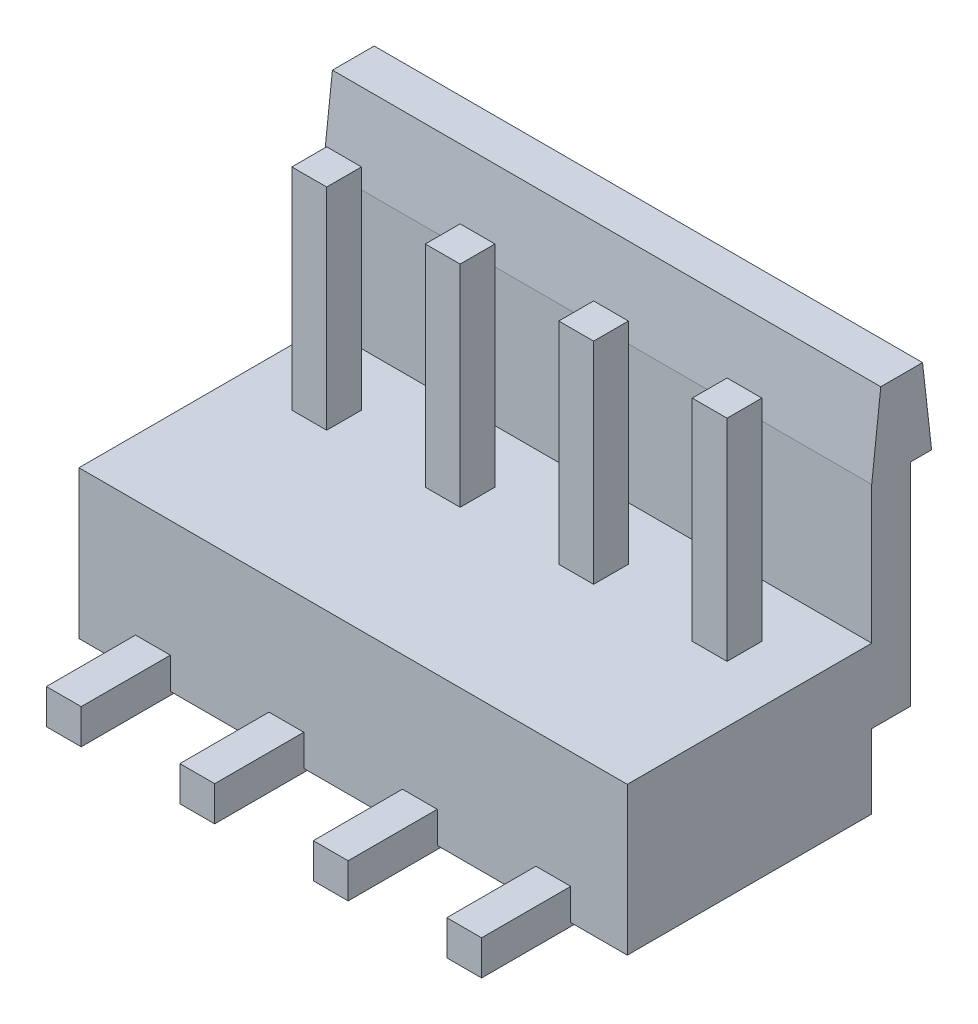
SolidWorks part; units mm, degrees
ref_plane "Front Plane" through (0, 0, 0) normal (0, 0, 1) x (1, 0, 0)
ref_plane "Top Plane" through (0, 0, 0) normal (0, 1, 0) x (1, 0, 0)
ref_plane "Right Plane" through (0, 0, 0) normal (1, 0, 0) x (0, 0, -1)
sketch "Sketch2" plane through (0, 0, 0) normal (1, 0, 0) x (0, 0, -1)
  line L0 (0, 0) -> (0, 3.95)
  line L1 (-7.02, 0) -> (0, 0)
  line L2 (-7.02, 0) -> (-7.02, -4.25)
  line L3 (-7.02, -4.25) -> (0, -4.25)
  line L4 (0, 0) -> (0, -4.25)
  line L5 (0, 3.95) -> (0.26, 6.25)
  line L6 (0.26, 6.25) -> (1.46, 6.25)
  line L7 (1.46, 6.25) -> (1.72, 3.95)
  line L8 (1.72, 3.95) -> (1.12, 3.95)
  line L9 (1.12, 3.95) -> (1.12, -2.125)
  line L10 (1.12, -2.125) -> (0, -2.125)
  dimension "D1" = 1.72
  dimension "D2" = 10.5
  dimension "D3" = 6.25
  dimension "D4" = 2.3
  dimension "D5" = 1.2
  dimension "D6" = 1.12
  dimension "D7" = 8.14
extrude "Boss-Extrude1" add sketch "Sketch2" along normal mid plane 15.75 contours L4 L1 L2 L3 | L10 L9 L8 L7 L6 L5 L0 L4
ref_plane "Plane1" through (5.75, 0, 0) normal (1, 0, 0) x (0, 0, -1)
sketch "Sketch3" plane through (5.75, 0, 0) normal (1, 0, 0) x (0, 0, -1)
  line L0 (-2.03, 6.05) -> (-2.03, -1.85)
  line L1 (-4.03, -3.85) -> (-9.58, -3.85)
  line L2 (-7.02, -4.25) -> (0, -4.25) construction
  arc A0 (-2.03, -1.85) -> (-4.03, -3.85) centre (-4.03, -1.85) cw
  dimension "D1" = 2
  dimension "D2" = 0.4
  dimension "D3" = 3.75
  dimension "D4" = 10.3
  dimension "D5" = 11.3
ref_plane "Plane2" through (0, 6.05, 0) normal (0, 1, 0) x (1, 0, 0)
sketch "Sketch4" plane through (0, 6.05, 0) normal (0, 1, 0) x (1, 0, 0)
  line L1 (6.25, -2.53) -> (5.25, -2.53)
  line L2 (6.25, -2.53) -> (6.25, -1.53)
  line L3 (6.25, -1.53) -> (5.25, -1.53)
  line L4 (5.25, -2.53) -> (5.25, -1.53)
  line L5 (6.25, -2.53) -> (5.25, -1.53) construction
  line L6 (6.25, -1.53) -> (5.25, -2.53) construction
  point P0 (5.75, -2.03)
  dimension "D1" = 1
sweep "Sweep1" add profiles "Sketch4" path "Sketch3"
pattern_linear "LPattern1" count 4 spacing 3.8333 along (-1, 0, 0) of "Sweep1"
